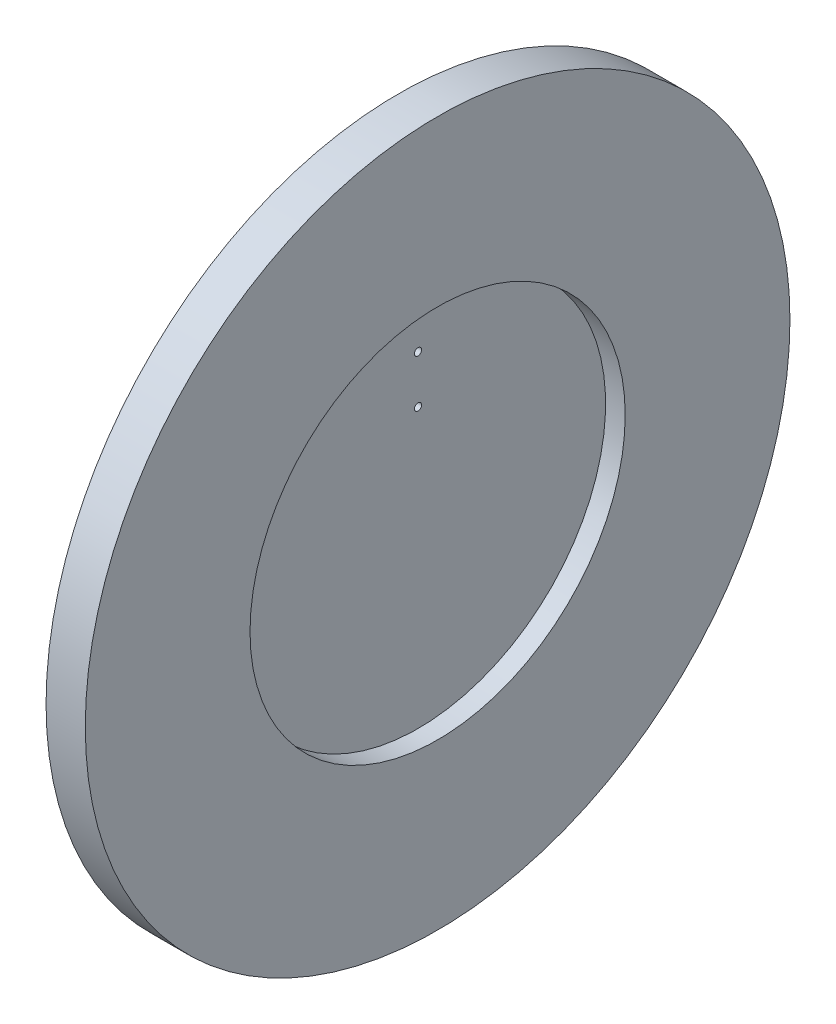
SolidWorks part; units mm, degrees
ref_plane "Front Plane" through (0, 0, 0) normal (0, 0, 1) x (1, 0, 0)
ref_plane "Top Plane" through (0, 0, 0) normal (0, 1, 0) x (1, 0, 0)
ref_plane "Right Plane" through (0, 0, 0) normal (1, 0, 0) x (0, 0, -1)
sketch "Sketch1" plane through (0, 0, 0) normal (1, 0, 0) x (0, 0, -1)
  circle A0 centre (0, 0) radius 89.825
  circle A1 centre (0, 0) radius 47.825
  dimension "D1" = 179.65
  dimension "D2" = 95.65
extrude "Boss-Extrude1" add sketch "Sketch1" along normal blind 10
sketch "Sketch3" plane through (0, 0, 0) normal (-1, 0, 0) x (0, 0, 1)
  circle A0 centre (0, 0) radius 47.825
  dimension "D1" = 95.65
extrude "tbh idk" add sketch "Sketch3" against normal blind 5
sketch "Sketch4" plane through (0, 0, 0) normal (-1, 0, 0) x (0, 0, 1)
  circle A0 centre (0, 0) radius 47.825
  dimension "D1" = 95.65
extrude "Extrusion to Fuel Man" add sketch "Sketch4" along normal blind 5
sketch "Ox Profile" plane through (-5, 0, 0) normal (-1, 0, 0) x (0, 0, 1)
  line L0 (-5.8915, 29.2826) -> (5.8915, 29.2826) construction
  circle A0 centre (0, 29.2826) radius 0.8262 construction
  circle A1 centre (0, 23.192) radius 0.9146
  circle A2 centre (0, 35.3732) radius 0.9146
  point P4 (0, 0)
  point P11 (0, 29.2826)
  dimension "D1" = 1.6524
  dimension "D3" = 1.8292
  dimension "D2" = 29.2826
  dimension "D4" = 6.0906
extrude "Ox Downcomer" cut sketch "Ox Profile" against normal up to next
equation "\"Flange_Dia\"= 179.65"
equation "\"Regen_Thickness\"= 1.5"
equation "\"Regen_To_Inner\"=2"
equation "\"Faceplate_Area\"=95.65"
equation "\"Regen_Rib_Thickness\"=1"
equation "\"Flange_Thickness\"= 10"
equation "\"Faceplate_To_Chamber_Extrusion\"=5"
equation "\"Injector_MCCN_O-Ring\"=3"
equation "\"Ox_Orifice\" = 1.829247371"
equation "\"Fuel_Orifice\"= 1.65242067"
equation "\"OxFuel_Dist_Downstream\"= 3"
equation "\"Fuel_Dist_From_Center\"=29.2826"
equation "\"OxFuel_HalfAngle\"=30"
equation "\"D1@Sketch1\"=\"Flange_Dia\""
equation "\"D2@Sketch1\"=\"Faceplate_Area\""
equation "\"D1@Boss-Extrude1\"=\"Flange_Thickness\""
equation "\"D1@Sketch3\"=\"Faceplate_Area\""
equation "\"D1@tbh idk\" = \"Flange_Thickness\" / 2"
equation "\"D1@Sketch4\"=\"Faceplate_Area\""
equation "\"D1@Extrusion to Fuel Man\" = \"Flange_Thickness\" / 2"
equation "\"D1@Ox Profile\" = \"Fuel_Orifice\""
equation "\"D2@Ox Profile\" = \"Fuel_Dist_From_Center\""
equation "\"D3@Ox Profile\" = \"Ox_Orifice\""
equation "\"D1@Flange\" = \"Flange_Thickness\""
equation "\"D1@Regen Slots Sketch\" = \"Regen_Rib_Thickness\""
equation "\"D2@Regen Slots Sketch\" = \"Regen_Thickness\""
equation "\"D3@Regen Slots Sketch\" = \"Regen_To_Inner\""
equation "\"D1@Faceplate Extrusion to Manifold Sketch\" = \"Faceplate_Area\""
equation "\"D1@Faceplate Extrusion to Chamber Sketch\" = \"Faceplate_Area\""
equation "\"D1@Faceplate Extrusion to Chamber\"=\"Faceplate_To_Chamber_Extrusion\""
equation "\"D1@O-Ring Slot Sketch\" = \"Faceplate_Area\""
equation "\"D2@O-Ring Slot Sketch\" = \"Injector_MCCN_O-Ring\""
equation "\"D1@O-Ring Slot\" =  ( \"Faceplate_To_Chamber_Extrusion\" )  +  ( \"Injector_MCCN_O-Ring\" / 2 ) "
equation "\"D1@Fuel Orifices Sketch\" = \"Ox_Orifice\""
equation "\"D2@Fuel Orifices Sketch\" = \"Fuel_Orifice\""
equation "\"D5@Fuel Orifices Sketch\" = \"Fuel_Dist_From_Center\""
equation "\"D3@Fuel Orifices Sketch\" = \"OxFuel_Dist_Downstream\""
equation "\"D4@Fuel Orifices Sketch\" = \"OxFuel_Dist_Downstream\""
equation "\"D1@Ox1 Profile\" = \"Ox_Orifice\""
equation "\"D1@Ox2 Profile\" = \"Ox_Orifice\""
equation "\"D1@Ox2 Guide Curve\" = \"OxFuel_HalfAngle\""
equation "\"D2@Ox1 Profile\" = \"OxFuel_Dist_Downstream\""
equation "\"D2@Ox2 Profile\"=\"OxFuel_Dist_Downstream\""
equation "\"D1@Ox1 Guide Curve\"=\"OxFuel_HalfAngle\""
equation "\"Thickness_FuelMan\"=5"
equation "\"D1@Faceplate Extrusion to Manifold\"=\"Thickness_FuelMan\""
equation "\"OxFuel_Dist_Upstream\"= ( ( \"Ox_Orifice\" / 2 ) + ( \"Fuel_Orifice\" / 2 ) + sqr ( \"OxFuel_Dist_Downstream\" ^ 2 + ( \"Thickness_FuelMan\" + \"Faceplate_To_Chamber_Extrusion\" ) ^ 2 ) ) / 2"
equation "\"D4@Ox Profile\"=\"OxFuel_Dist_Upstream\""
